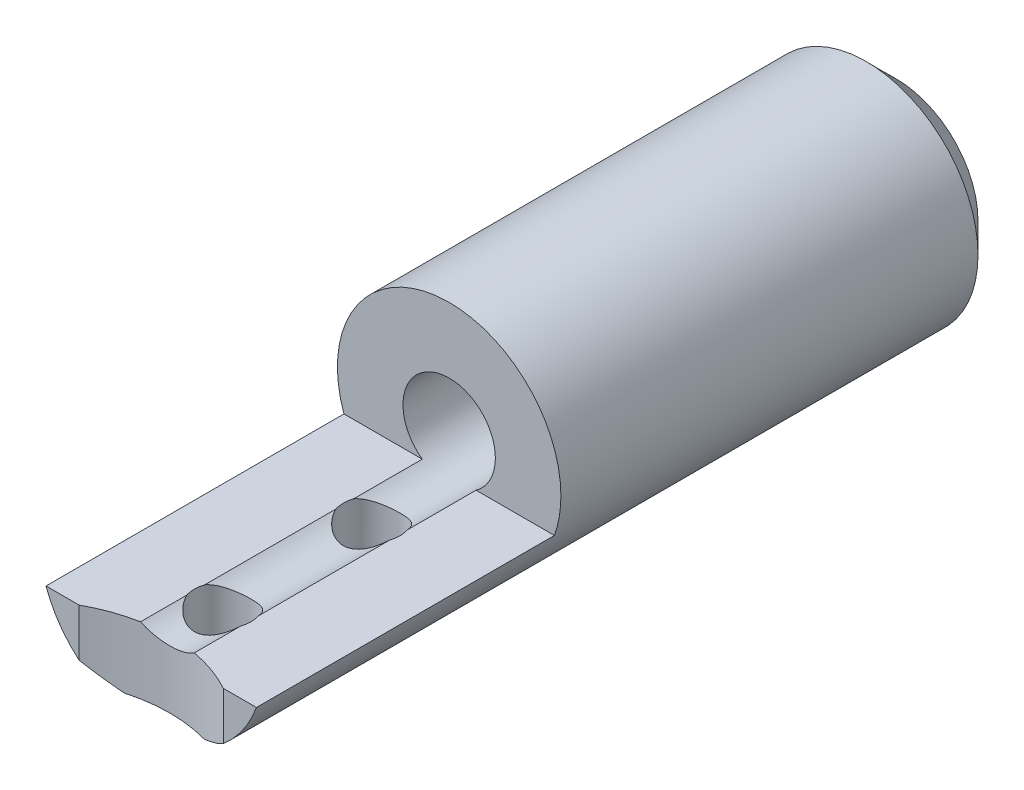
SolidWorks part; units mm, degrees
material "1060 Alloy"
ref_plane "Front" through (0, 0, 0) normal (0, 0, 1) x (1, 0, 0)
ref_plane "Top" through (0, 0, 0) normal (0, 1, 0) x (1, 0, 0)
ref_plane "Right" through (0, 0, 0) normal (1, 0, 0) x (0, 0, -1)
sketch "Sketch1" plane through (0, 0, 0) normal (0, 0, 1) x (1, 0, 0)
  circle A0 centre (0, 0) radius 3.937
  circle A1 centre (0, 0) radius 9.525
extrude "Extrude1" add sketch "Sketch1" against normal blind 63.5
sketch "Sketch2" plane through (0, 0, 0) normal (0, 0, 1) x (1, 0, 0)
  line L0 (0, 3.2004) -> (0, -5.0881) construction
  line L1 (-9.525, -3.2004) -> (9.525, -3.2004)
  line L3 (9.525, 3.2004) -> (9.525, -3.2004)
  line L4 (-9.525, 3.2004) -> (-9.525, -3.2004)
  arc A1 (9.525, 3.2004) -> (-9.525, 3.2004) centre (0, 0.4024) ccw
  point P3 (0, -3.2004)
extrude "Cut-Extrude1" cut sketch "Sketch2" against normal blind 25.4
sketch "Sketch3" plane through (0, 0, 0) normal (0, 0, 1) x (1, 0, 0)
  line L0 (0, -3.937) -> (0, -9.525)
  line L1 (0, -9.525) -> (6.5942, -9.525)
  line L2 (6.5942, -9.525) -> (6.5942, -8.89)
  line L3 (6.5942, -8.89) -> (-6.1872, -8.89)
  line L4 (-6.1872, -8.89) -> (-6.1872, -9.525)
  line L5 (-6.1872, -9.525) -> (0, -9.525)
  arc A0 (-2.2929, -3.2004) -> (2.2929, -3.2004) centre (0, 0) ccw construction
  arc A1 (-8.9712, -3.2004) -> (8.9712, -3.2004) centre (0, 0) ccw construction
  dimension "D1" = 5.588
extrude "Cut-Extrude2" cut sketch "Sketch3" against normal up to surface (25.4 mm away) contours L1 L2 L3 L4 L5 up to face at (0, 1.7653, -25.4)
sketch "Sketch4" plane through (0, -8.89, 0) normal (0, -1, 0) x (1, 0, 0)
  circle A0 centre (0, -6.096) radius 2.413
  circle A1 centre (0, -18.796) radius 2.413
  circle A2 centre (0, -38.9955) radius 1.8923
  circle A3 centre (0, -51.6955) radius 1.8923
extrude "Cut-Extrude3" cut sketch "Sketch4" against normal mid plane 12.7
chamfer "Chamfer2" distance 2.54 angle 45 1 edges at (9.525, 0, -63.5)
sketch "Sketch5" plane through (0, -8.89, 0) normal (0, -1, 0) x (1, 0, 0)
  circle A0 centre (0, 11.1125) radius 12.7
extrude "Cut-Extrude4" cut sketch "Sketch5" against normal through all
